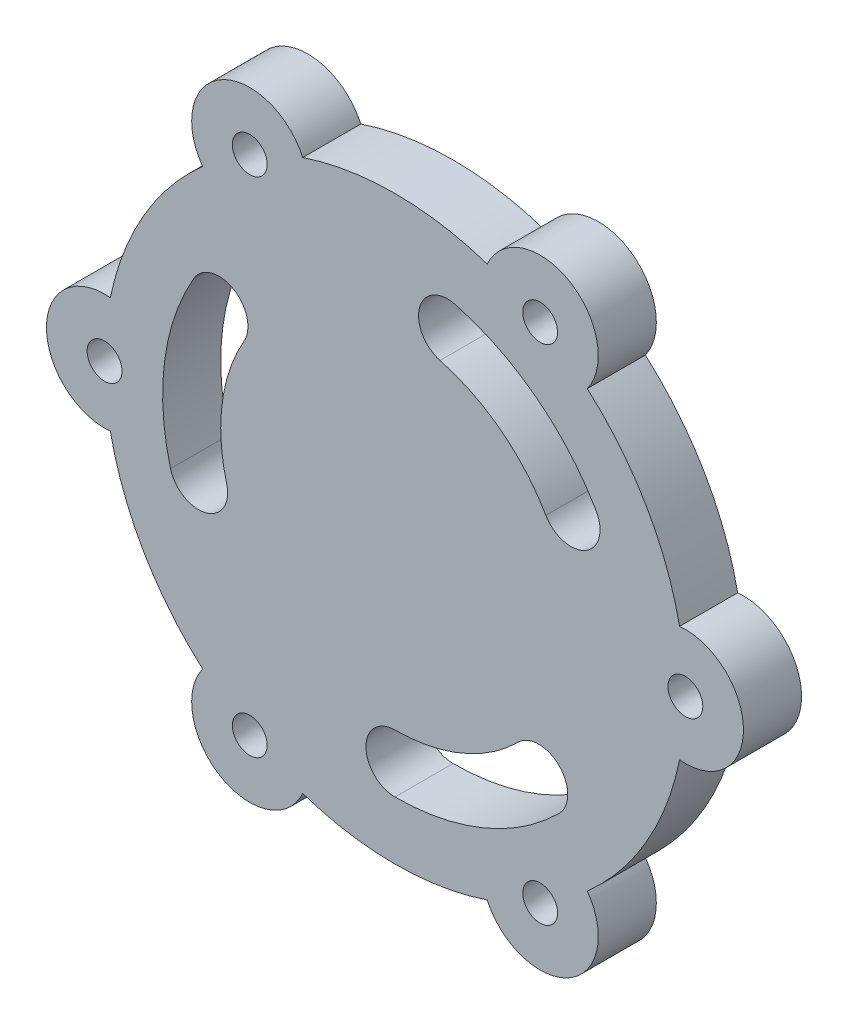
SolidWorks part; units mm, degrees
ref_plane "Front Plane" through (0, 0, 0) normal (0, 0, 1) x (1, 0, 0)
ref_plane "Top Plane" through (0, 0, 0) normal (0, 1, 0) x (1, 0, 0)
ref_plane "Right Plane" through (0, 0, 0) normal (1, 0, 0) x (0, 0, -1)
sketch "Sketch1" plane through (0, 0, 0) normal (0, 0, 1) x (1, 0, 0)
  arc A0 (49, 9.9499) -> (33.1168, 37.4603) centre (0, 0) ccw
  circle A1 centre (50, 0) radius 3
  arc A2 (49, -9.9499) -> (49, 9.9499) centre (50, 0) ccw
  circle A3 centre (25, -43.3013) radius 3
  arc A4 (15.8832, -47.4102) -> (33.1168, -37.4603) centre (25, -43.3013) ccw
  circle A5 centre (-25, -43.3013) radius 3
  arc A6 (-33.1168, -37.4603) -> (-15.8832, -47.4102) centre (-25, -43.3013) ccw
  circle A7 centre (-50, 0) radius 3
  arc A8 (-49, 9.9499) -> (-49, -9.9499) centre (-50, 0) ccw
  circle A9 centre (-25, 43.3013) radius 3
  arc A10 (-15.8832, 47.4102) -> (-33.1168, 37.4603) centre (-25, 43.3013) ccw
  circle A11 centre (25, 43.3013) radius 3
  arc A12 (33.1168, 37.4603) -> (15.8832, 47.4102) centre (25, 43.3013) ccw
  arc A13 (34.641, 20) -> (10.3528, 38.637) centre (0, 0) ccw
  arc A15 (15.8832, 47.4102) -> (-15.8832, 47.4102) centre (0, 0) ccw
  arc A16 (25.9808, 15) -> (7.7646, 28.9778) centre (0, 0) ccw
  arc A17 (-33.1168, 37.4603) -> (-49, 9.9499) centre (0, 0) ccw
  arc A18 (10.3528, 38.637) -> (7.7646, 28.9778) centre (9.0587, 33.8074) ccw
  arc A19 (-49, -9.9499) -> (-33.1168, -37.4603) centre (0, 0) ccw
  arc A20 (25.9808, 15) -> (34.641, 20) centre (30.3109, 17.5) ccw
  arc A21 (-15.8832, -47.4102) -> (15.8832, -47.4102) centre (0, 0) ccw
  arc A22 (0, -40) -> (28.2843, -28.2843) centre (0, 0) ccw
  arc A23 (33.1168, -37.4603) -> (49, -9.9499) centre (0, 0) ccw
  arc A24 (0, -30) -> (21.2132, -21.2132) centre (0, 0) ccw
  arc A25 (0, -30) -> (0, -40) centre (0, -35) ccw
  arc A26 (28.2843, -28.2843) -> (21.2132, -21.2132) centre (24.7487, -24.7487) ccw
  arc A27 (-34.641, 20) -> (-38.637, -10.3528) centre (0, 0) ccw
  arc A28 (-25.9808, 15) -> (-28.9778, -7.7646) centre (0, 0) ccw
  arc A29 (-25.9808, 15) -> (-34.641, 20) centre (-30.3109, 17.5) ccw
  arc A30 (-38.637, -10.3528) -> (-28.9778, -7.7646) centre (-33.8074, -9.0587) ccw
  point P29 (0, 0)
  point P47 (0, 0)
  dimension "D1" = 6
  dimension "D3" = 50
  dimension "D2" = 6
  dimension "D4" = 10
  dimension "D5" = 40
  dimension "D6" = 30
  dimension "D7" = 7.7646
extrude "Boss-Extrude1" add sketch "Sketch1" along normal blind 10
